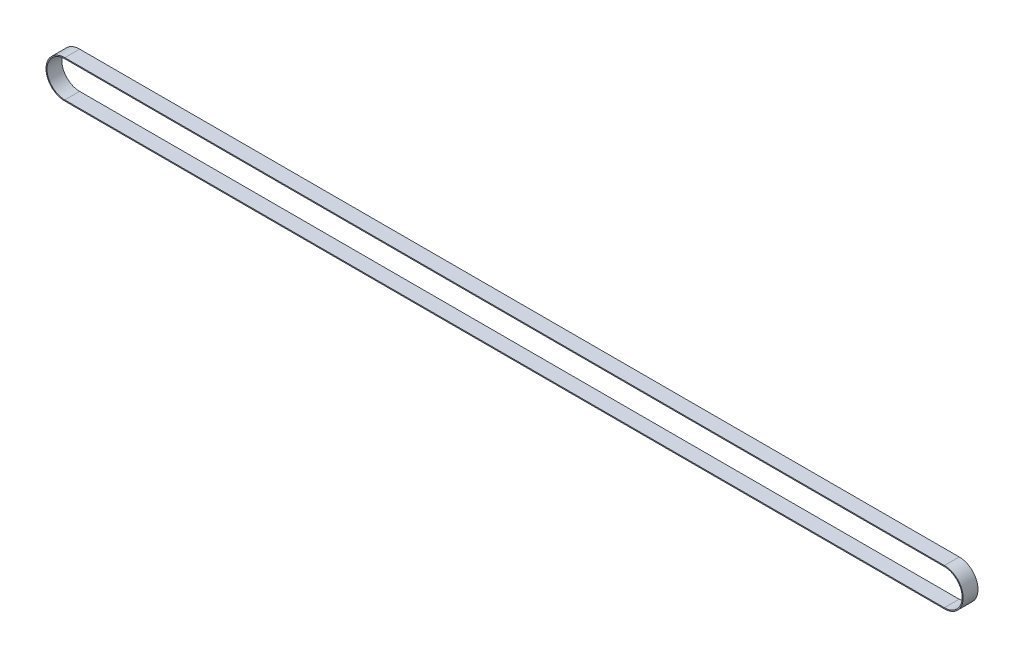
SolidWorks part; units mm, degrees
ref_plane "Front" through (0, 0, 0) normal (0, 0, 1) x (1, 0, 0)
ref_plane "Top" through (0, 0, 0) normal (0, 1, 0) x (1, 0, 0)
ref_plane "Right" through (0, 0, 0) normal (1, 0, 0) x (0, 0, -1)
sketch "草图1" plane through (0, 0, 0) normal (0, 0, 1) x (1, 0, 0)
  line L0 (0, 0) -> (889, 0) construction
  line L1 (0, -19) -> (889, -19)
  line L2 (889, 19) -> (0, 19)
  line L3 (889, 18) -> (0, 18)
  line L4 (0, -18) -> (889, -18)
  arc A0 (0, 18) -> (0, -18) centre (0, 0) ccw
  arc A1 (0, 19) -> (0, -19) centre (0, 0) ccw
  arc A2 (889, -18) -> (889, 18) centre (889, 0) ccw
  arc A3 (889, -19) -> (889, 19) centre (889, 0) ccw
  dimension "D1" = 36
  dimension "D2" = 1
  dimension "D3" = 1
  dimension "D4" = 36
  dimension "D5" = 889
extrude "凸台-拉伸1" add sketch "草图1" along normal blind 15
